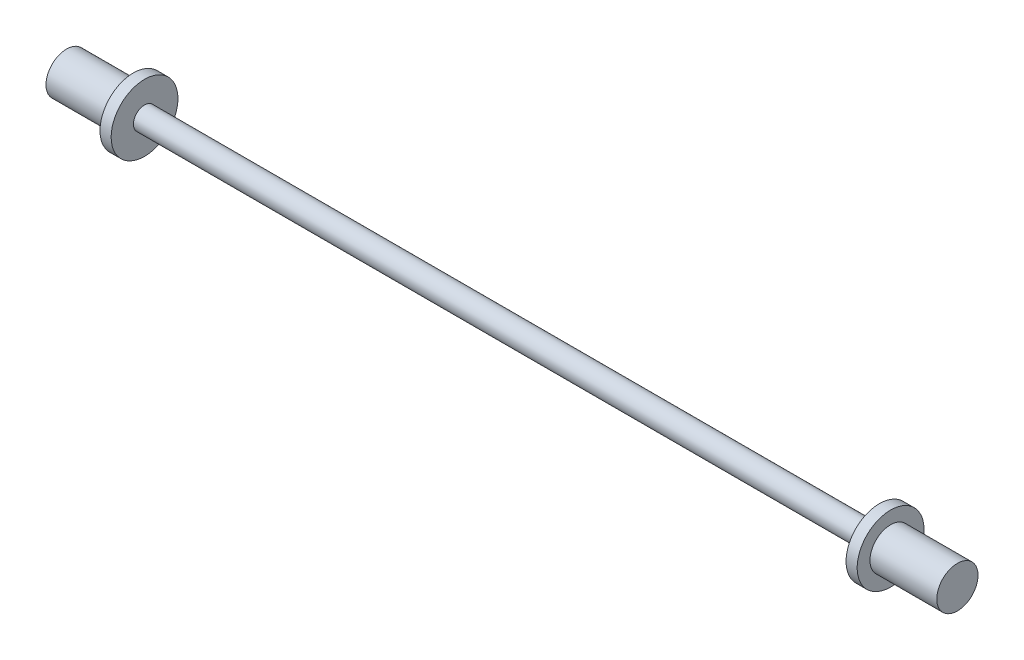
SolidWorks part; units mm, degrees
material "6061 Alloy"
ref_plane "Front Plane" through (0, 0, 0) normal (0, 0, 1) x (1, 0, 0)
ref_plane "Top Plane" through (0, 0, 0) normal (0, 1, 0) x (1, 0, 0)
ref_plane "Right Plane" through (0, 0, 0) normal (1, 0, 0) x (0, 0, -1)
sketch "Sketch2" plane through (0, 0, 0) normal (1, 0, 0) x (0, 0, -1)
  circle A0 centre (0, 0) radius 6.35
  dimension "D1" = 12.7
extrude "Boss-Extrude1" add sketch "Sketch2" along normal blind 247.65 and the other way blind 171.45
sketch "Sketch3" plane through (247.65, 0, 0) normal (1, 0, 0) x (0, 0, -1)
  circle A0 centre (0, 0) radius 19.05
  dimension "D1" = 38.1
extrude "Boss-Extrude2" add sketch "Sketch3" along normal blind 6.35
sketch "Sketch7" plane through (-171.45, 0, 0) normal (-1, 0, 0) x (0, 0, 1)
  circle A0 centre (0, 0) radius 19.05 construction
  circle A3 centre (0, 0) radius 19.05
extrude "Boss-Extrude4" add sketch "Sketch7" along normal blind 6.35
sketch "Sketch9" plane through (-177.8, 0, 0) normal (-1, 0, 0) x (0, 0, 1)
  circle A0 centre (0, 0) radius 11.77
  dimension "D1" = 23.54
extrude "Boss-Extrude6" add sketch "Sketch9" along normal blind 38.1
sketch "Sketch10" plane through (254, 0, 0) normal (1, 0, 0) x (0, 0, -1)
  circle A0 centre (0, 0) radius 11.77 construction
  circle A1 centre (0, 0) radius 11.77
extrude "Boss-Extrude7" add sketch "Sketch10" along normal blind 38.1
